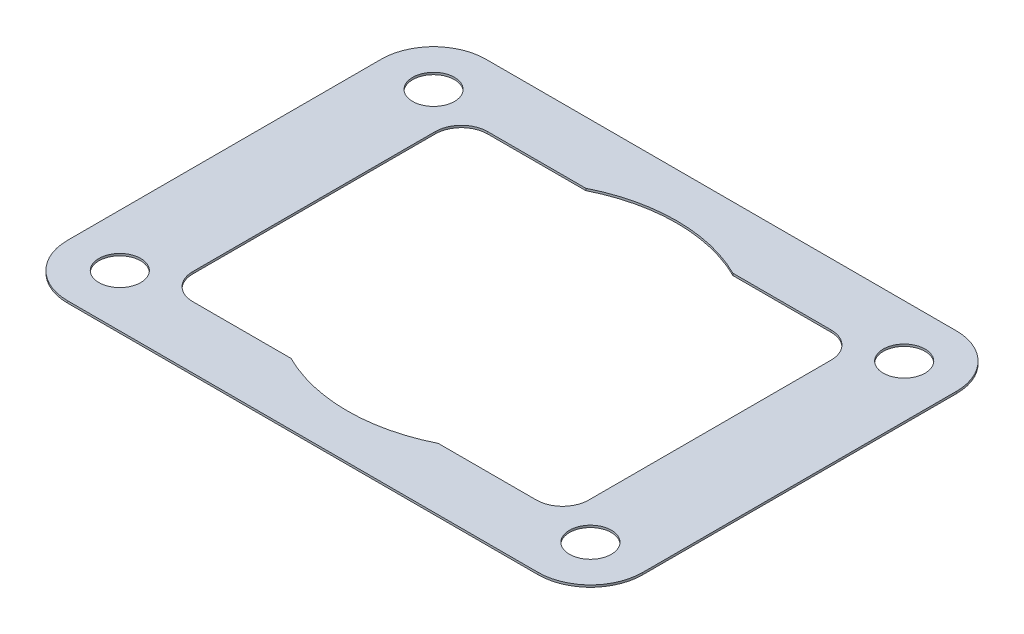
SolidWorks part; units mm, degrees
material "VITON"
ref_plane "Front Plane" through (0, 0, 0) normal (0, 0, 1) x (1, 0, 0)
ref_plane "Top Plane" through (0, 0, 0) normal (0, 1, 0) x (1, 0, 0)
ref_plane "Right Plane" through (0, 0, 0) normal (1, 0, 0) x (0, 0, -1)
sketch "Sketch1" plane through (0, 0, 0) normal (0, 1, 0) x (1, 0, 0)
  line L1 (69.85, -50.8) -> (-69.85, -50.8)
  line L2 (69.85, -50.8) -> (69.85, 50.8)
  line L3 (69.85, 50.8) -> (-69.85, 50.8)
  line L4 (-69.85, -50.8) -> (-69.85, 50.8)
  line L5 (69.85, -50.8) -> (-69.85, 50.8) construction
  line L6 (69.85, 50.8) -> (-69.85, -50.8) construction
  point P0 (0, 0)
  dimension "D1" = 139.7
  dimension "D2" = 101.6
extrude "Boss-Extrude1" add sketch "Sketch1" along normal blind 0.508
fillet "Fillet1" radius 12.7 4 edges at (-69.85, 0.254, -50.8) (69.85, 0.254, -50.8) (69.85, 0.254, 50.8) (-69.85, 0.254, 50.8)
sketch "Sketch2" plane through (0, 0.508, 0) normal (0, 1, 0) x (1, 0, 0)
  line L1 (48.0695, -35.7886) -> (-48.0695, -35.7886)
  line L2 (48.0695, -35.7886) -> (48.0695, 35.7886)
  line L3 (48.0695, 35.7886) -> (-48.0695, 35.7886)
  line L4 (-48.0695, -35.7886) -> (-48.0695, 35.7886)
  line L5 (48.0695, -35.7886) -> (-48.0695, 35.7886) construction
  line L6 (48.0695, 35.7886) -> (-48.0695, -35.7886) construction
  point P0 (0, 0)
  dimension "D1" = 96.139
  dimension "D2" = 71.5772
extrude "Cut-Extrude1" cut sketch "Sketch2" against normal through all
fillet "Fillet2" radius 6.35 4 edges at (48.0695, 0.254, 35.7886) (-48.0695, 0.254, 35.7886) (48.0695, 0.254, -35.7886) (-48.0695, 0.254, -35.7886)
sketch "Sketch3" plane through (0, 0.508, 0) normal (0, 1, 0) x (1, 0, 0)
  circle A0 centre (-57.15, 38.1) radius 5.08
extrude "Cut-Extrude2" cut sketch "Sketch3" against normal through all
mirror "Mirror1" about plane through (0, 0, 0) normal (1, 0, 0) of "Cut-Extrude2"
mirror "Mirror2" about plane through (0, 0, 0) normal (0, 0, 1) of "Mirror1", "Cut-Extrude2"
sketch "Sketch4" plane through (0, 0.508, 0) normal (0, 1, 0) x (1, 0, 0)
  circle A0 centre (0, 0) radius 40.005
extrude "Cut-Extrude3" cut sketch "Sketch4" against normal through all
